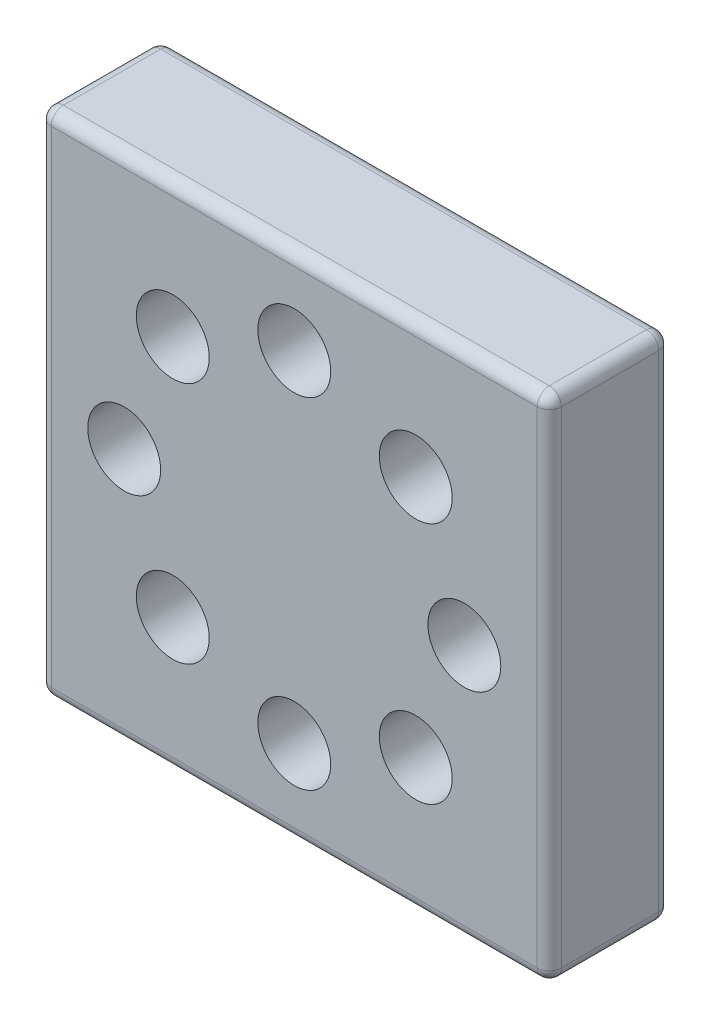
SolidWorks part; units mm, degrees
ref_plane "Front Plane" through (0, 0, 0) normal (0, 0, 1) x (1, 0, 0)
ref_plane "Top Plane" through (0, 0, 0) normal (0, 1, 0) x (1, 0, 0)
ref_plane "Right Plane" through (0, 0, 0) normal (1, 0, 0) x (0, 0, -1)
sketch "Sketch1" plane through (0, 0, 0) normal (0, 0, 1) x (1, 0, 0)
  line L0 (-10.5, 0) -> (10.5, 0) construction
  line L1 (-10.5, 10.5) -> (10.5, 10.5)
  line L2 (-10.5, 10.5) -> (-10.5, -10.5)
  line L3 (-10.5, -10.5) -> (10.5, -10.5)
  line L4 (10.5, 10.5) -> (10.5, -10.5)
  line L5 (-10.5, 10.5) -> (10.5, -10.5) construction
  line L6 (-10.5, -10.5) -> (10.5, 10.5) construction
  line L7 (0, 10.5) -> (0, -10.5) construction
  circle A0 centre (-5, 5) radius 1.5
  circle A1 centre (5, 5) radius 1.5
  circle A2 centre (5, -5) radius 1.5
  circle A3 centre (-5, -5) radius 1.5
  circle A4 centre (0, 7) radius 1.5
  circle A5 centre (7, 0) radius 1.5
  circle A6 centre (-7, 0) radius 1.5
  circle A7 centre (0, -7) radius 1.5
  point P0 (0, 0)
  dimension "D7" = 3
  dimension "D8" = 3
  dimension "D9" = 3
  dimension "D10" = 3
  dimension "D15" = 3
  dimension "D16" = 3
  dimension "D17" = 3
  dimension "D18" = 3
  dimension "D1" = 21
  dimension "D2" = 21
  dimension "D3" = 10
  dimension "D4" = 10
  dimension "D5" = 10
  dimension "D6" = 10
  dimension "D11" = 7
  dimension "D12" = 7
  dimension "D13" = 7
  dimension "D14" = 7
extrude "Boss-Extrude1" add sketch "Sketch1" along normal blind 5
fillet "Fillet1" radius 0.5 12 edges at (10.5, -10.5, 2.5) (10.5, 0, 0) (0, -10.5, 0) (0, -10.5, 5) (-10.5, -10.5, 2.5) (10.5, 0, 5) (10.5, 10.5, 2.5) (0, 10.5, 0) (-10.5, 0, 0) (-10.5, 0, 5) (0, 10.5, 5) (-10.5, 10.5, 2.5)
